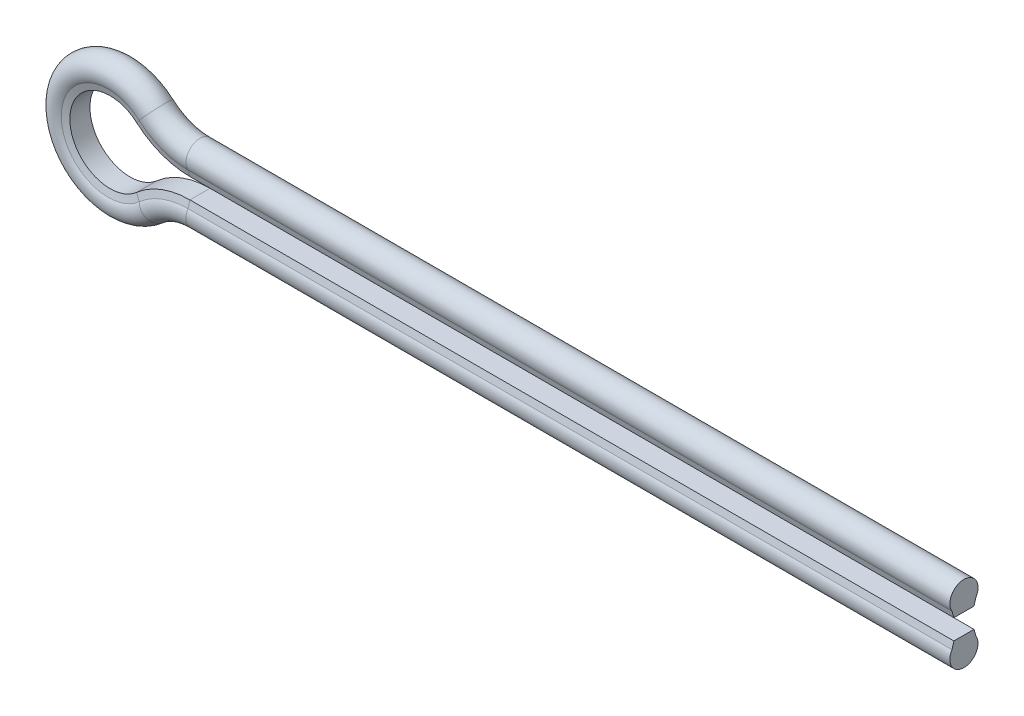
SolidWorks part; units mm, degrees
ref_plane "Front Plane" through (0, 0, 0) normal (0, 0, 1) x (1, 0, 0)
ref_plane "Top Plane" through (0, 0, 0) normal (0, 1, 0) x (1, 0, 0)
ref_plane "Right Plane" through (0, 0, 0) normal (1, 0, 0) x (0, 0, -1)
sketch "Sketch1" plane through (0, 0, 0) normal (0, 0, 1) x (1, 0, 0)
  line L0 (0, 0) -> (-94.9197, 0)
  line L2 (0, -2.5) -> (-94.9197, -2.5)
  arc A1 (-101.534, 2.5) -> (-101.534, -5) centre (-104.8412, -1.25) ccw
  arc A2 (-94.9197, -2.5) -> (-101.534, -5) centre (-94.9197, -12.5) ccw
  arc A3 (-101.534, 2.5) -> (-94.9197, 0) centre (-94.9197, 10) ccw
  dimension "D3" = 5
  dimension "D4" = 20
  dimension "D5" = 20
sketch "Sketch2" plane through (0, 0, 0) normal (1, 0, 0) x (0, 0, -1)
  line L0 (-1.25, 0) -> (1.25, 0)
  line L3 (-1.25, 0) -> (-1.4858, 0.8255)
  line L4 (1.25, 0) -> (1.4858, 0.8255)
  arc A1 (1.4858, 0.8255) -> (-1.4858, 0.8255) centre (0, 1.75) ccw
  point P4 (0, 0)
  dimension "D1" = 2.5
sweep "Sweep2" add profiles "Sketch2" path "Sketch1"
